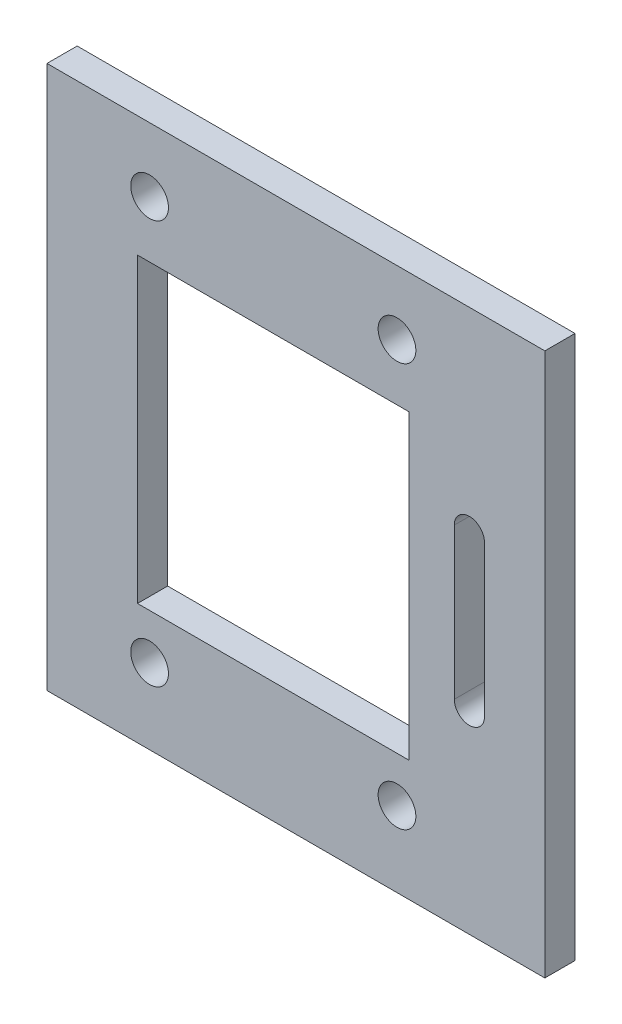
SolidWorks part; units mm, degrees
ref_plane "Front Plane" through (0, 0, 0) normal (0, 0, 1) x (1, 0, 0)
ref_plane "Top Plane" through (0, 0, 0) normal (0, 1, 0) x (1, 0, 0)
ref_plane "Right Plane" through (0, 0, 0) normal (1, 0, 0) x (0, 0, -1)
sketch "Sketch1" plane through (0, 0, 0) normal (0, 0, 1) x (1, 0, 0)
  line L1 (0, 0) -> (66, 0)
  line L2 (0, 0) -> (0, 72)
  line L3 (0, 72) -> (66, 72)
  line L4 (66, 0) -> (66, 72)
  line L5 (12, 16) -> (48, 16)
  line L6 (12, 16) -> (12, 56)
  line L7 (12, 56) -> (48, 56)
  line L8 (48, 16) -> (48, 56)
  dimension "D1" = 66
  dimension "D2" = 72
  dimension "D3" = 36
  dimension "D4" = 12
  dimension "D5" = 40
  dimension "D6" = 16
extrude "Boss-Extrude1" add sketch "Sketch1" along normal blind 4
sketch "Sketch2" plane through (0, 0, 4) normal (0, 0, 1) x (1, 0, 0)
  line L0 (66, 72) -> (0, 72) construction
  line L1 (0, 0) -> (66, 0) construction
  circle A0 centre (46.4, 63.5) radius 2.5
  circle A1 centre (13.6, 63.5) radius 2.5
  circle A2 centre (13.6, 10) radius 2.5
  circle A3 centre (46.4, 10) radius 2.5
  dimension "D5" = 5
  dimension "D6" = 5
  dimension "D11" = 5
  dimension "D12" = 5
  dimension "D1" = 8.5
  dimension "D2" = 8.5
  dimension "D3" = 1.6
  dimension "D4" = 1.6
  dimension "D7" = 10
  dimension "D8" = 10
  dimension "D9" = 1.6
  dimension "D10" = 1.6
extrude "Cut-Extrude1" cut sketch "Sketch2" against normal blind 10
sketch "Sketch4" plane through (0, 0, 4) normal (0, 0, 1) x (1, 0, 0)
  line L0 (56, 46) -> (56, 26) construction
  line L1 (58, 46) -> (58, 26)
  line L2 (54, 46) -> (54, 26)
  line L3 (66, 72) -> (0, 72) construction
  line L4 (66, 0) -> (66, 72) construction
  arc A0 (58, 46) -> (54, 46) centre (56, 46) ccw
  arc A1 (54, 26) -> (58, 26) centre (56, 26) ccw
  point P2 (56, 36)
  dimension "D3" = 2
  dimension "D1" = 20
  dimension "D2" = 36
  dimension "D4" = 10
extrude "Cut-Extrude3" cut sketch "Sketch4" against normal blind 10
